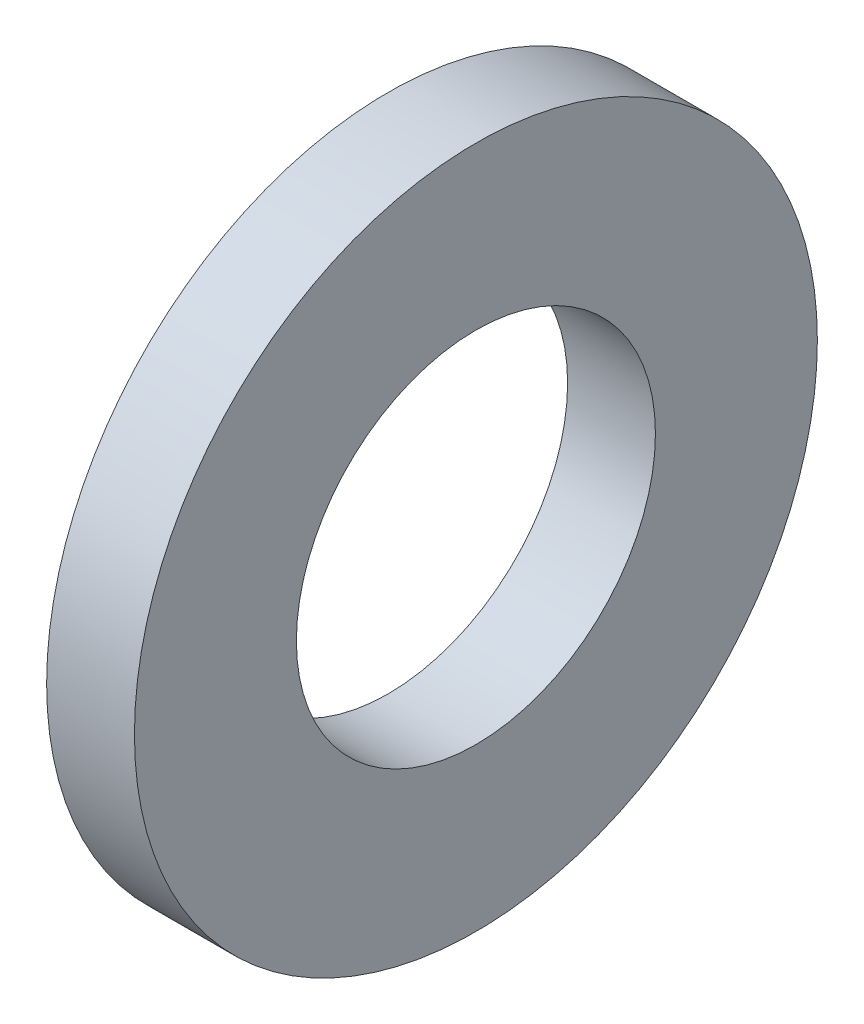
SolidWorks part; units mm, degrees
ref_plane "Plane1" through (0, 0, 0) normal (0, 0, 1) x (1, 0, 0)
ref_plane "Plane2" through (0, 0, 0) normal (0, 1, 0) x (1, 0, 0)
ref_plane "Plane3" through (0, 0, 0) normal (1, 0, 0) x (0, 0, -1)
sketch "Sketch1" plane through (0, 0, 0) normal (0, 0, 1) x (1, 0, 0)
  line L0 (-34.925, 0) -> (9.525, 0) construction
  line L1 (0, 1.84) -> (0, 3.5)
  line L2 (0, 3.5) -> (-0.9, 3.5)
  line L3 (-0.9, 3.5) -> (-0.9, 1.84)
  line L4 (-0.9, 1.84) -> (0, 1.84)
  dimension "Thickness" = 0.9
  dimension "Inside_dia" = 3.68
  dimension "Outside_dia" = 7
revolve "Base-Revolve" add sketch "Sketch1" angle 360 about L0
